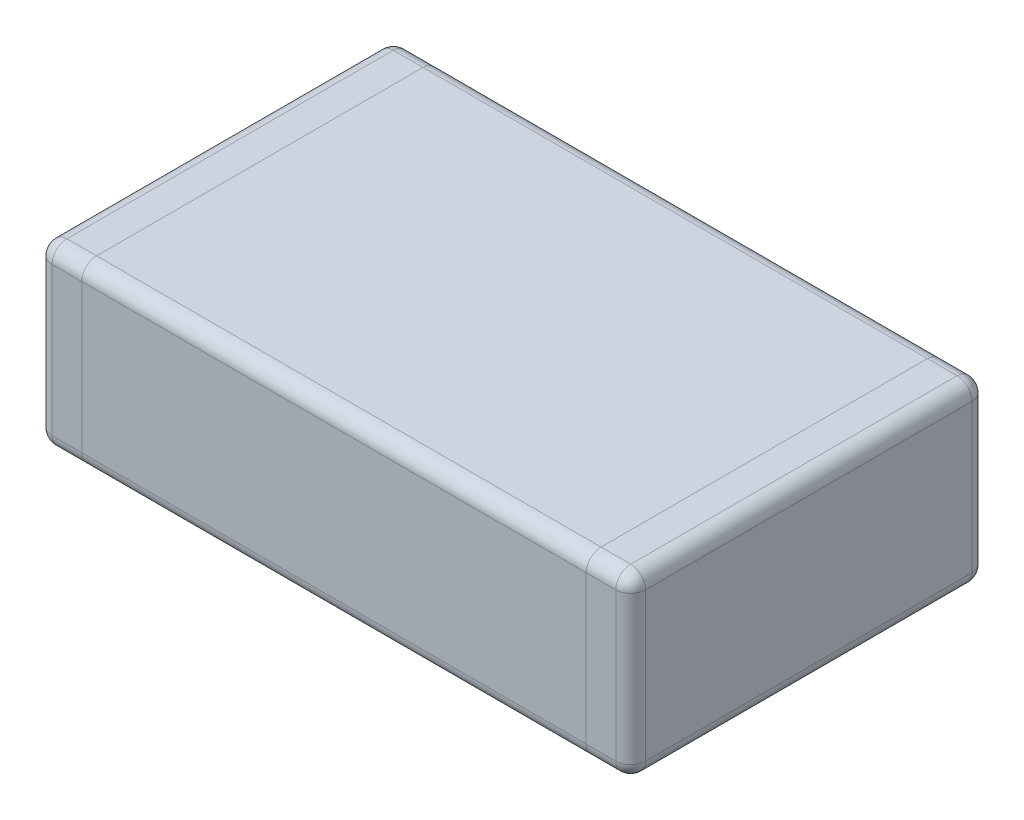
SolidWorks part; units mm, degrees
ref_plane "Front Plane" through (0, 0, 0) normal (0, 0, 1) x (1, 0, 0)
ref_plane "Top Plane" through (0, 0, 0) normal (0, 1, 0) x (1, 0, 0)
ref_plane "Right Plane" through (0, 0, 0) normal (1, 0, 0) x (0, 0, -1)
sketch "Sketch1" plane through (0, 0, 0) normal (0, 1, 0) x (1, 0, 0)
  line L1 (-1, -0.6) -> (1, -0.6)
  line L2 (-1, -0.6) -> (-1, 0.6)
  line L3 (-1, 0.6) -> (1, 0.6)
  line L4 (1, -0.6) -> (1, 0.6)
  line L5 (-1, -0.6) -> (1, 0.6) construction
  line L6 (-1, 0.6) -> (1, -0.6) construction
  point P0 (0, 0)
  dimension "D1" = 2
  dimension "D2" = 1.2
extrude "Extrude1" add sketch "Sketch1" along normal blind 0.6
fillet "Fillet1" radius 0.05 12 edges at (1, 0.3, -0.6) (-1, 0.3, -0.6) (-1, 0.3, 0.6) (1, 0.3, 0.6) (0, 0.6, 0.6) (-1, 0.6, 0) (0, 0.6, -0.6) (1, 0.6, 0) (0, 0, -0.6) (-1, 0, 0) (0, 0, 0.6) (1, 0, 0)
sketch "Sketch2" plane through (0, 0, 0) normal (0, 1, 0) x (1, 0, 0)
  line L1 (-0.85, -0.6) -> (0.85, -0.6)
  line L2 (-0.85, -0.6) -> (-0.85, 0.6)
  line L3 (-0.85, 0.6) -> (0.85, 0.6)
  line L4 (0.85, -0.6) -> (0.85, 0.6)
  line L6 (0, 0.55) -> (0, -0.6635) construction
  line L7 (0.95, 0.55) -> (-0.95, 0.55) construction
  line L9 (0.95, -0.6) -> (-0.95, -0.6) construction
  line L11 (-0.95, 0.6) -> (0.95, 0.6) construction
  line L13 (-1, -0.55) -> (-1, 0.55) construction
  dimension "D1" = 0.15
split line "Split Line3"
